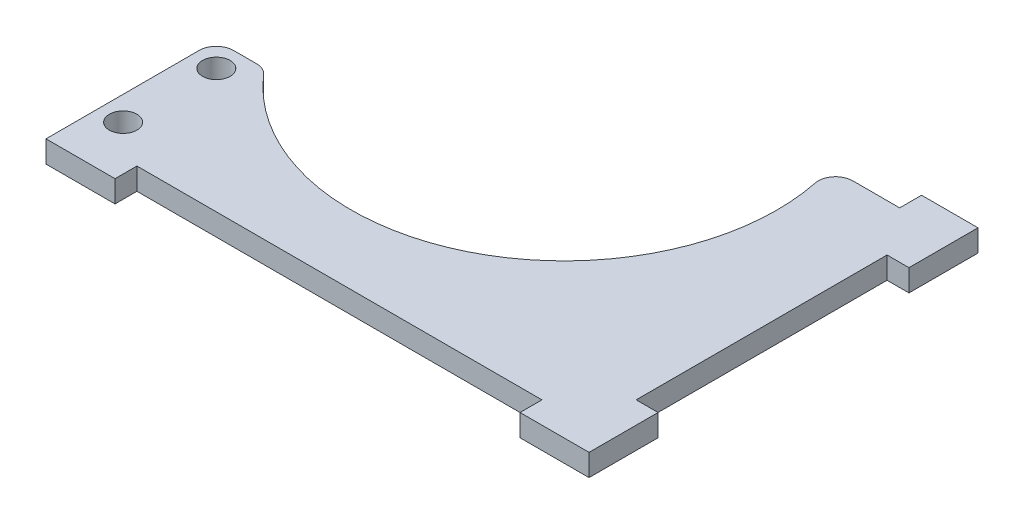
SolidWorks part; units mm, degrees
ref_plane "Front Plane" through (0, 0, 0) normal (0, 0, 1) x (1, 0, 0)
ref_plane "Top Plane" through (0, 0, 0) normal (0, 1, 0) x (1, 0, 0)
ref_plane "Right Plane" through (0, 0, 0) normal (1, 0, 0) x (0, 0, -1)
sketch "Sketch1" plane through (0, 0, 0) normal (0, 1, 0) x (1, 0, 0)
  line L0 (-78.675, -56.35) -> (-58.675, -56.35)
  line L1 (-58.675, -56.35) -> (-58.675, -50)
  line L2 (-58.675, -50) -> (58.675, -50)
  line L3 (58.675, -50) -> (58.675, -56.35)
  line L4 (58.675, -56.35) -> (78.675, -56.35)
  line L5 (78.675, -56.35) -> (78.675, -36.35)
  line L6 (78.675, -36.35) -> (72.325, -36.35)
  line L7 (72.325, -36.35) -> (72.325, 36.35)
  line L8 (72.325, 36.35) -> (78.675, 36.35)
  line L9 (78.675, 36.35) -> (78.675, 56.35)
  line L10 (78.675, 56.35) -> (62.325, 56.35)
  line L11 (62.325, 56.35) -> (62.325, 50)
  line L12 (62.325, 50) -> (42.325, 50)
  line L13 (-78.675, -56.35) -> (-78.675, -7)
  line L14 (-78.675, -7) -> (-64.675, -7)
  arc A0 (-64.675, -7) -> (42.325, 50) centre (-16.6151, 31.7121) ccw
  circle A1 centre (-71.675, -41) radius 4
  circle A2 centre (-71.675, -14) radius 4
  point P21 (-71.675, -10)
  point P22 (-71.675, -7)
  point P23 (-71.675, -45)
  point P24 (-67.675, -41)
  point P25 (-75.675, -14)
  point P26 (0, -50)
  point P28 (72.325, 0)
  point P30 (-16.6151, -30)
  dimension "D2" = 8
  dimension "D1" = 20
  dimension "D3" = 5
  dimension "D4" = 6.35
  dimension "D5" = 40
  dimension "D6" = 3
  dimension "D7" = 3
  dimension "D8" = 140
  dimension "D9" = 100
  dimension "D10" = 20
  dimension "D11" = 10
  dimension "D12" = 20
extrude "Boss-Extrude1" add sketch "Sketch1" along normal mid plane 6.35
fillet "Fillet1" radius 5 3 edges at (42.325, 0, -50) (-78.675, 0, 7) (-64.675, 0, 7)
